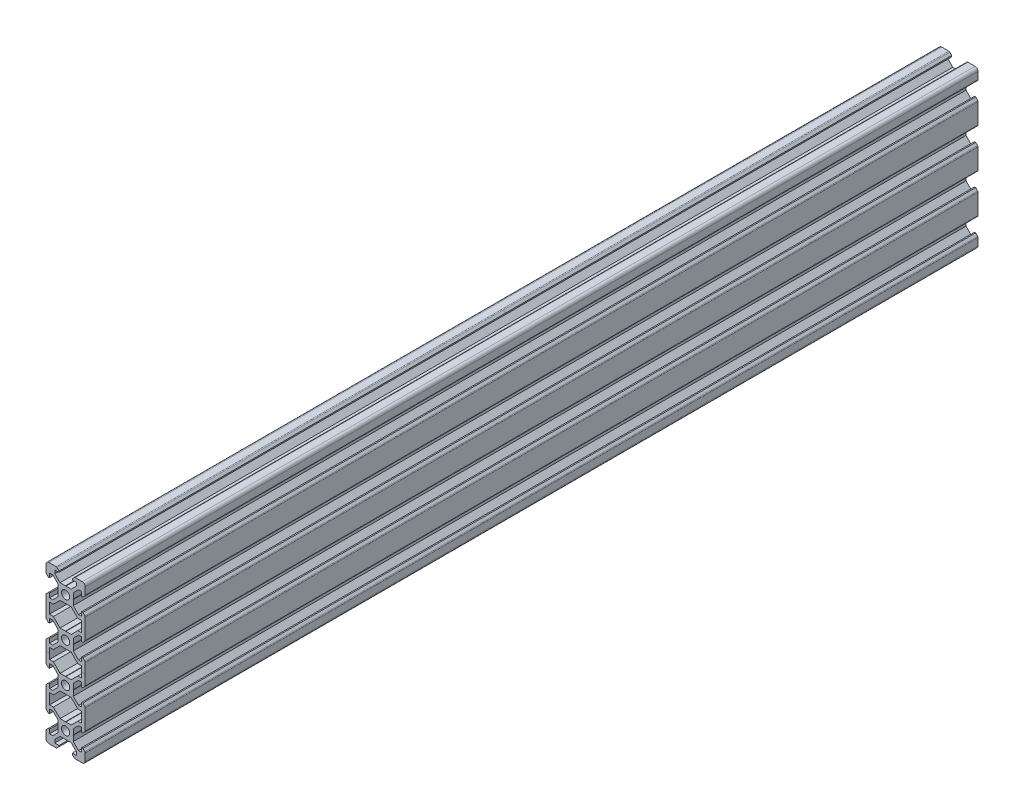
SolidWorks part; units mm, degrees
material "6063-T5"
ref_plane "Front" through (0, 0, 0) normal (0, 0, 1) x (1, 0, 0)
ref_plane "Top" through (0, 0, 0) normal (0, 1, 0) x (1, 0, 0)
ref_plane "Right" through (0, 0, 0) normal (1, 0, 0) x (0, 0, -1)
sketch "Sketch1" plane through (0, 0, 0) normal (0, 0, 1) x (1, 0, 0)
  line L0 (-8.5, 10) -> (-10, 8.5) construction
  line L1 (-8.5, 10) -> (-4.8628, 10)
  line L2 (-10, 8.5) -> (-10, 4.8628)
  line L3 (25.9287, -20) -> (-28.3599, -20) construction
  line L4 (10, 8.5) -> (10, 4.8628)
  line L5 (-10, 10) -> (10, -10) construction
  line L6 (-10, -10) -> (10, 10) construction
  line L7 (8.2, -5.5) -> (8.2, -3.3865)
  line L8 (-8.2, -5.5) -> (-8.2, -3.3865)
  line L9 (-5.5, 8.2) -> (-3.3865, 8.2)
  line L10 (-8.2, -12.7) -> (-8.2, -7.3)
  line L11 (-3.9005, 2.8395) -> (-6.561, 5.5)
  line L12 (-6.561, 5.5) -> (-8.2, 5.5)
  line L13 (-2.8395, -3.9005) -> (-0.1, -3.9005)
  line L14 (-3.9005, -2.8395) -> (-3.9005, -0.1)
  line L15 (-2.8395, 3.9005) -> (-0.1, 3.9005)
  line L16 (3.9005, -2.8395) -> (3.9005, -0.1)
  line L17 (-8.2, 3.3865) -> (-8.81, 3.3865)
  line L18 (-8.81, 3.3865) -> (-9.7976, 4.3741)
  line L19 (8.5, 10) -> (10, 8.5) construction
  line L20 (-2.8395, 3.9005) -> (-5.5, 6.561)
  line L21 (-5.5, 6.561) -> (-5.5, 8.2)
  line L22 (-3.3865, 8.2) -> (-3.3865, 8.81)
  line L23 (-3.3865, 8.81) -> (-4.3741, 9.7976)
  line L24 (0, 24.069) -> (0, -33.8154) construction
  line L25 (3.3865, 8.81) -> (4.3741, 9.7976)
  line L26 (3.3865, 8.2) -> (3.3865, 8.81)
  line L27 (5.5, 6.561) -> (5.5, 8.2)
  line L28 (2.8395, 3.9005) -> (5.5, 6.561)
  line L29 (3.3865, 8.2) -> (5.5, 8.2)
  line L30 (4.8628, 10) -> (8.5, 10)
  line L31 (-0.1, 3.9005) -> (0, 3.8005)
  line L32 (0.1, 3.9005) -> (0, 3.8005)
  line L33 (0.1, 3.9005) -> (2.8395, 3.9005)
  line L34 (25.9287, 0) -> (-28.3459, 0) construction
  line L35 (-0.1, -3.9005) -> (0, -3.8005)
  line L36 (0.1, -3.9005) -> (0, -3.8005)
  line L37 (0.1, -3.9005) -> (2.8395, -3.9005)
  line L38 (-3.9005, 0.1) -> (-3.8005, 0)
  line L39 (-3.8005, 0) -> (-3.9005, -0.1)
  line L40 (-3.9005, 0.1) -> (-3.9005, 2.8395)
  line L41 (3.9005, 0.1) -> (3.8005, 0)
  line L42 (3.8005, 0) -> (3.9005, -0.1)
  line L43 (3.9005, 0.1) -> (3.9005, 2.8395)
  line L44 (8.81, 3.3865) -> (9.7976, 4.3741)
  line L45 (8.2, 3.3865) -> (8.81, 3.3865)
  line L46 (6.561, 5.5) -> (8.2, 5.5)
  line L47 (3.9005, 2.8395) -> (6.561, 5.5)
  line L48 (2.8395, -3.9005) -> (5.5, -6.561)
  line L49 (3.9005, -2.8395) -> (6.561, -5.5)
  line L50 (-2.8395, -3.9005) -> (-5.5, -6.561)
  line L51 (-3.9005, -2.8395) -> (-6.561, -5.5)
  line L52 (6.561, -5.5) -> (8.2, -5.5)
  line L53 (-6.561, -5.5) -> (-8.2, -5.5)
  line L54 (-8.81, -3.3865) -> (-9.7976, -4.3741)
  line L55 (-8.2, -3.3865) -> (-8.81, -3.3865)
  line L56 (8.81, -3.3865) -> (9.7976, -4.3741)
  line L57 (8.2, -3.3865) -> (8.81, -3.3865)
  line L58 (8.2, 3.3865) -> (8.2, 5.5)
  line L59 (10, -4.8628) -> (10, -15.1372)
  line L60 (-8.2, 3.3865) -> (-8.2, 5.5)
  line L61 (-10, -4.8628) -> (-10, -15.1372)
  line L62 (-28.3459, -10) -> (-10, -10) construction
  line L63 (-3.9005, -20.1) -> (-3.9005, -22.8395)
  line L64 (-3.9005, -20.1) -> (-3.8005, -20)
  line L65 (-3.8005, -20) -> (-3.9005, -19.9)
  line L66 (3.9005, -20.1) -> (3.9005, -22.8395)
  line L67 (3.9005, -20.1) -> (3.8005, -20)
  line L68 (3.8005, -20) -> (3.9005, -19.9)
  line L69 (6.561, -14.5) -> (8.2, -14.5)
  line L70 (3.9005, -17.1605) -> (6.561, -14.5)
  line L71 (3.9005, -17.1605) -> (3.9005, -19.9)
  line L72 (-3.9005, -17.1605) -> (-3.9005, -19.9)
  line L73 (-3.9005, -17.1605) -> (-6.561, -14.5)
  line L74 (-6.561, -14.5) -> (-8.2, -14.5)
  line L75 (-8.2, -16.6135) -> (-8.81, -16.6135)
  line L76 (-8.81, -16.6135) -> (-9.7976, -15.6259)
  line L77 (8.2, -16.6135) -> (8.81, -16.6135)
  line L78 (8.81, -16.6135) -> (9.7976, -15.6259)
  line L79 (-2.8395, -16.0995) -> (-5.5, -13.439)
  line L80 (-2.8395, -16.0995) -> (-0.1, -16.0995)
  line L81 (-0.1, -16.0995) -> (0, -16.1995)
  line L82 (0.1, -16.0995) -> (0, -16.1995)
  line L83 (0.1, -16.0995) -> (2.8395, -16.0995)
  line L84 (2.8395, -16.0995) -> (5.5, -13.439)
  line L85 (-8.2, -16.6135) -> (-8.2, -14.5)
  line L86 (8.2, -16.6135) -> (8.2, -14.5)
  line L87 (2.8395, -23.9005) -> (5.5, -26.561)
  line L88 (-2.8395, -23.9005) -> (-5.5, -26.561)
  line L89 (-0.1, -23.9005) -> (0, -23.8005)
  line L90 (0.1, -23.9005) -> (0, -23.8005)
  line L91 (0.1, -23.9005) -> (2.8395, -23.9005)
  line L92 (-2.8395, -23.9005) -> (-0.1, -23.9005)
  line L93 (-8.2, -23.3865) -> (-8.2, -25.5)
  line L94 (-8.2, -23.3865) -> (-8.81, -23.3865)
  line L95 (-8.81, -23.3865) -> (-9.7976, -24.3741)
  line L96 (8.2, -23.3865) -> (8.2, -25.5)
  line L97 (8.2, -23.3865) -> (8.81, -23.3865)
  line L98 (8.81, -23.3865) -> (9.7976, -24.3741)
  line L99 (8.2, -27.3) -> (8.2, -32.7)
  line L100 (10, -35.1372) -> (10, -24.8628)
  line L101 (-10, -35.1372) -> (-10, -24.8628)
  line L102 (-8.2, -27.3) -> (-8.2, -32.7)
  line L103 (3.9005, -22.8395) -> (6.561, -25.5)
  line L104 (-3.9005, -22.8395) -> (-6.561, -25.5)
  line L105 (6.239, -27.3) -> (8.2, -27.3)
  line L106 (-6.239, -27.3) -> (-8.2, -27.3)
  line L107 (-6.561, -25.5) -> (-8.2, -25.5)
  line L108 (6.561, -25.5) -> (8.2, -25.5)
  line L109 (5.5, -26.561) -> (6.239, -27.3)
  line L110 (-5.5, -26.561) -> (-6.239, -27.3)
  line L111 (8.2, -34.5) -> (8.2, -36.6135)
  line L112 (8.2, -36.6135) -> (8.81, -36.6135)
  line L113 (8.81, -36.6135) -> (9.7976, -35.6259)
  line L114 (-8.2, -34.5) -> (-8.2, -36.6135)
  line L115 (-6.239, -7.3) -> (-8.2, -7.3)
  line L116 (-5.5, -6.561) -> (-6.239, -7.3)
  line L117 (6.239, -7.3) -> (8.2, -7.3)
  line L118 (5.5, -6.561) -> (6.239, -7.3)
  line L119 (-6.239, -12.7) -> (-8.2, -12.7)
  line L120 (-5.5, -13.439) -> (-6.239, -12.7)
  line L121 (5.5, -13.439) -> (6.239, -12.7)
  line L122 (6.239, -12.7) -> (8.2, -12.7)
  line L123 (8.2, -12.7) -> (8.2, -7.3)
  line L124 (-8.2, -36.6135) -> (-8.81, -36.6135)
  line L125 (10, -10) -> (25.9287, -10) construction
  line L126 (-8.81, -36.6135) -> (-9.7976, -35.6259)
  line L127 (-0.1, -56.0995) -> (0, -56.1995)
  line L128 (-0.1, -36.0995) -> (0, -36.1995)
  line L129 (0.1, -36.0995) -> (0, -36.1995)
  line L130 (0.1, -36.0995) -> (2.8395, -36.0995)
  line L131 (-6.561, -34.5) -> (-8.2, -34.5)
  line L132 (6.561, -34.5) -> (8.2, -34.5)
  line L133 (6.239, -32.7) -> (8.2, -32.7)
  line L134 (-6.239, -32.7) -> (-8.2, -32.7)
  line L135 (-5.5, -33.439) -> (-6.239, -32.7)
  line L136 (5.5, -33.439) -> (6.239, -32.7)
  line L137 (-26.6965, -30) -> (27.5921, -30) construction
  line L138 (0.1, -56.0995) -> (0, -56.1995)
  line L139 (0.1, -56.0995) -> (2.8395, -56.0995)
  line L140 (-2.8395, -56.0995) -> (-0.1, -56.0995)
  line L141 (0, -60) -> (0, -71.7864) construction
  line L142 (-3.8005, -60) -> (-3.9005, -59.9)
  line L143 (-3.9005, -60.1) -> (-3.8005, -60)
  line L144 (10, -68.5) -> (10, -64.8628)
  line L145 (0.1, -63.9005) -> (0, -63.8005)
  line L146 (-0.1, -63.9005) -> (0, -63.8005)
  line L147 (-2.8395, -63.9005) -> (-0.1, -63.9005)
  line L148 (0.1, -63.9005) -> (2.8395, -63.9005)
  line L149 (3.9005, -60.1) -> (3.9005, -62.8395)
  line L150 (3.9005, -60.1) -> (3.8005, -60)
  line L151 (3.8005, -60) -> (3.9005, -59.9)
  line L152 (3.9005, -57.1605) -> (3.9005, -59.9)
  line L153 (4.8628, -70) -> (8.5, -70)
  line L154 (3.3865, -68.81) -> (4.3741, -69.7976)
  line L155 (3.3865, -68.2) -> (3.3865, -68.81)
  line L156 (3.3865, -68.2) -> (5.5, -68.2)
  line L157 (-0.1, -43.9005) -> (0, -43.8005)
  line L158 (0.1, -43.9005) -> (0, -43.8005)
  line L159 (-2.8395, -43.9005) -> (-0.1, -43.9005)
  line L160 (0.1, -43.9005) -> (2.8395, -43.9005)
  line L161 (3.9005, -40.1) -> (3.8005, -40)
  line L162 (3.8005, -40) -> (3.9005, -39.9)
  line L163 (3.9005, -37.1605) -> (3.9005, -39.9)
  line L164 (3.9005, -40.1) -> (3.9005, -42.8395)
  line L165 (-2.8395, -36.0995) -> (-0.1, -36.0995)
  line L166 (-2.8395, -43.9005) -> (-5.5, -46.561)
  line L167 (-3.9005, -37.1605) -> (-3.9005, -39.9)
  line L168 (-3.8005, -40) -> (-3.9005, -39.9)
  line L169 (-3.9005, -40.1) -> (-3.8005, -40)
  line L170 (-3.9005, -42.8395) -> (-6.561, -45.5)
  line L171 (2.8395, -43.9005) -> (5.5, -46.561)
  line L172 (3.9005, -42.8395) -> (6.561, -45.5)
  line L173 (3.9005, -37.1605) -> (6.561, -34.5)
  line L174 (2.8395, -36.0995) -> (5.5, -33.439)
  line L175 (-3.9005, -42.8395) -> (-3.9005, -40.1)
  line L176 (-6.561, -34.5) -> (-3.9005, -37.1605)
  line L177 (-5.5, -33.439) -> (-2.8395, -36.0995)
  line L178 (5.5, -66.561) -> (5.5, -68.2)
  line L179 (6.561, -65.5) -> (8.2, -65.5)
  line L180 (8.2, -63.3865) -> (8.2, -65.5)
  line L181 (8.81, -63.3865) -> (9.7976, -64.3741)
  line L182 (8.2, -63.3865) -> (8.81, -63.3865)
  line L183 (-8.2, -63.3865) -> (-8.81, -63.3865)
  line L184 (-8.81, -63.3865) -> (-9.7976, -64.3741)
  line L185 (-8.2, -63.3865) -> (-8.2, -65.5)
  line L186 (-6.561, -65.5) -> (-8.2, -65.5)
  line L187 (-5.5, -66.561) -> (-5.5, -68.2)
  line L188 (-5.5, -68.2) -> (-3.3865, -68.2)
  line L189 (-3.3865, -68.2) -> (-3.3865, -68.81)
  line L190 (-3.3865, -68.81) -> (-4.3741, -69.7976)
  line L191 (-10, -68.5) -> (-10, -64.8628)
  line L192 (-8.5, -70) -> (-4.8628, -70)
  line L193 (-8.2, -43.3865) -> (-8.81, -43.3865)
  line L194 (-8.81, -43.3865) -> (-9.7976, -44.3741)
  line L195 (-10, -55.1372) -> (-10, -44.8628)
  line L196 (-8.81, -56.6135) -> (-9.7976, -55.6259)
  line L197 (-8.2, -56.6135) -> (-8.81, -56.6135)
  line L198 (8.2, -56.6135) -> (8.81, -56.6135)
  line L199 (8.81, -56.6135) -> (9.7976, -55.6259)
  line L200 (8.2, -43.3865) -> (8.81, -43.3865)
  line L201 (8.81, -43.3865) -> (9.7976, -44.3741)
  line L202 (10, -55.1372) -> (10, -44.8628)
  line L203 (-8.2, -47.3) -> (-8.2, -52.7)
  line L204 (8.2, -47.3) -> (8.2, -52.7)
  line L205 (-6.239, -52.7) -> (-8.2, -52.7)
  line L206 (6.239, -52.7) -> (8.2, -52.7)
  line L207 (-6.561, -54.5) -> (-8.2, -54.5)
  line L208 (6.561, -54.5) -> (8.2, -54.5)
  line L209 (-3.9005, -60.1) -> (-3.9005, -62.8395)
  line L210 (-2.8395, -56.0995) -> (-5.5, -53.439)
  line L211 (3.9005, -57.1605) -> (6.561, -54.5)
  line L212 (2.8395, -56.0995) -> (5.5, -53.439)
  line L213 (5.5, -53.439) -> (6.239, -52.7)
  line L214 (-5.5, -53.439) -> (-6.239, -52.7)
  line L215 (-8.2, -43.3865) -> (-8.2, -45.5)
  line L216 (8.2, -43.3865) -> (8.2, -45.5)
  line L217 (-2.8395, -63.9005) -> (-5.5, -66.561)
  line L218 (-3.9005, -62.8395) -> (-6.561, -65.5)
  line L219 (2.8395, -63.9005) -> (5.5, -66.561)
  line L220 (3.9005, -62.8395) -> (6.561, -65.5)
  line L221 (-8.2, -54.5) -> (-8.2, -56.6135)
  line L222 (8.2, -54.5) -> (8.2, -56.6135)
  line L223 (6.239, -47.3) -> (8.2, -47.3)
  line L224 (-6.239, -47.3) -> (-8.2, -47.3)
  line L225 (-6.561, -45.5) -> (-8.2, -45.5)
  line L226 (-5.5, -46.561) -> (-6.239, -47.3)
  line L227 (6.561, -45.5) -> (8.2, -45.5)
  line L228 (5.5, -46.561) -> (6.239, -47.3)
  line L229 (-3.9005, -57.1605) -> (-3.9005, -59.9)
  line L230 (-3.9005, -57.1605) -> (-6.561, -54.5)
  circle A0 centre (0, 0) radius 2.1
  arc A1 (-8.5, 10) -> (-10, 8.5) centre (-8.5, 8.5) ccw
  arc A2 (10, 8.5) -> (8.5, 10) centre (8.5, 8.5) ccw
  arc A3 (-4.3741, 9.7976) -> (-4.8628, 10) centre (-4.8628, 9.3088) ccw
  arc A4 (4.8628, 10) -> (4.3741, 9.7976) centre (4.8628, 9.3088) ccw
  circle A5 centre (0, -20) radius 2.1
  arc A6 (9.7976, 4.3741) -> (10, 4.8628) centre (9.3088, 4.8628) ccw
  arc A7 (-10, 4.8628) -> (-9.7976, 4.3741) centre (-9.3088, 4.8628) ccw
  arc A8 (-10, -4.8628) -> (-9.7976, -4.3741) centre (-9.3088, -4.8628) cw
  arc A9 (9.7976, -4.3741) -> (10, -4.8628) centre (9.3088, -4.8628) cw
  arc A10 (-10, -15.1372) -> (-9.7976, -15.6259) centre (-9.3088, -15.1372) ccw
  arc A11 (9.7976, -15.6259) -> (10, -15.1372) centre (9.3088, -15.1372) ccw
  arc A12 (-10, -24.8628) -> (-9.7976, -24.3741) centre (-9.3088, -24.8628) cw
  arc A13 (9.7976, -24.3741) -> (10, -24.8628) centre (9.3088, -24.8628) cw
  arc A14 (9.7976, -35.6259) -> (10, -35.1372) centre (9.3088, -35.1372) ccw
  arc A15 (-10, -35.1372) -> (-9.7976, -35.6259) centre (-9.3088, -35.1372) ccw
  circle A16 centre (0, -40) radius 2.1
  circle A17 centre (0, -60) radius 2.1
  arc A18 (10, -68.5) -> (8.5, -70) centre (8.5, -68.5) cw
  arc A19 (4.8628, -70) -> (4.3741, -69.7976) centre (4.8628, -69.3088) cw
  arc A20 (9.7976, -64.3741) -> (10, -64.8628) centre (9.3088, -64.8628) cw
  arc A21 (-10, -64.8628) -> (-9.7976, -64.3741) centre (-9.3088, -64.8628) cw
  arc A22 (-4.3741, -69.7976) -> (-4.8628, -70) centre (-4.8628, -69.3088) cw
  arc A23 (-8.5, -70) -> (-10, -68.5) centre (-8.5, -68.5) cw
  arc A24 (-10, -44.8628) -> (-9.7976, -44.3741) centre (-9.3088, -44.8628) cw
  arc A25 (-10, -55.1372) -> (-9.7976, -55.6259) centre (-9.3088, -55.1372) ccw
  arc A26 (9.7976, -55.6259) -> (10, -55.1372) centre (9.3088, -55.1372) ccw
  arc A27 (9.7976, -44.3741) -> (10, -44.8628) centre (9.3088, -44.8628) cw
  point P17 (-9.25, 9.25)
  point P21 (9.25, 9.25)
  point P181 (-10, -30)
  dimension "D2" = 4.2
  dimension "D4" = 1.5
  dimension "D3" = 20
  dimension "D5" = 0.529
  dimension "D6" = 6.773
  dimension "D7" = 90
  dimension "D8" = 11
  dimension "D9" = 0.61
  dimension "D10" = 0.1
  dimension "D11" = 0.1
  dimension "D12" = 0.1
  dimension "D13" = 0.1
  dimension "D14" = 5.679
  dimension "D15" = 1.639
  dimension "D16" = 1.8
  dimension "D17" = 90
  dimension "D18" = 6.773
  dimension "D19" = 90
  dimension "D20" = 20
  dimension "D21" = 1.8
extrude "Boss-Extrude2" add sketch "Sketch1" along normal blind 455
sketch "Sketch2" plane through (0, 0, 455) normal (0, 0, 1) x (1, 0, 0)
  line L0 (-10, -30) -> (10, -30)
  line L1 (-10, -24.8628) -> (-10, -35.1372) construction
  line L2 (10, -35.1372) -> (10, -24.8628) construction
split line "SideFixture1 - SplitLine"
sketch "Sketch3" plane through (0, 0, 0) normal (0, 0, -1) x (-1, 0, 0)
  line L0 (-10, -30) -> (10, -30)
  line L1 (-10, -35.1372) -> (-10, -24.8628) construction
  line L2 (10, -24.8628) -> (10, -35.1372) construction
split line "SideFixture2 - SplitLine"
sketch "Sketch4" plane through (0, 10, 0) normal (0, 1, 0) x (1, 0, 0)
  line L0 (8.5, -227.5) -> (-8.5, -227.5)
  line L1 (8.5, -455) -> (8.5, 0) construction
  line L2 (-8.5, -455) -> (-8.5, 0) construction
split line "SideFixture3 - SplitLine"
equation "\"base-xwidth\" = 455mm"
equation "\"base-yheight\"= 500mm"
equation "\"base-zdepth\"= 500mm"
equation "\"D1@Boss-Extrude2\"=\"base-xwidth\""
